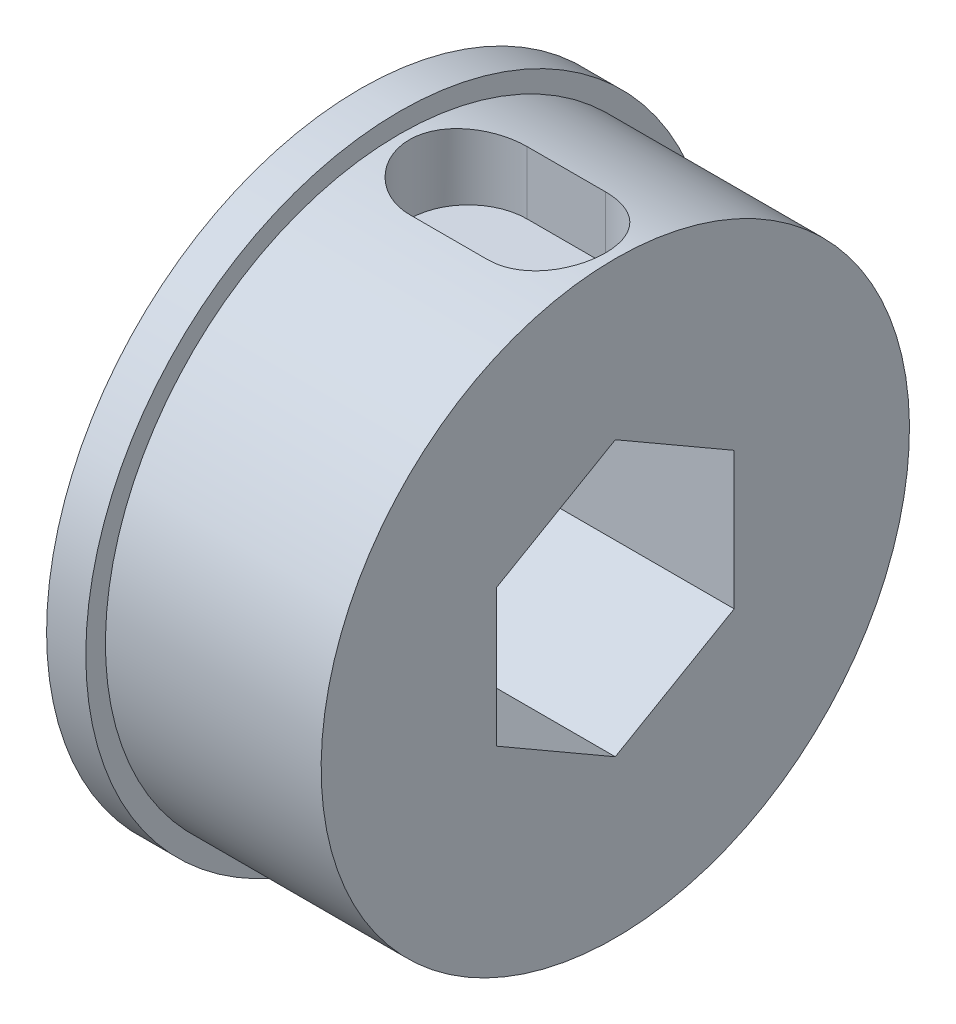
SolidWorks part; units mm, degrees
ref_plane "Front Plane" through (0, 0, 0) normal (0, 0, 1) x (1, 0, 0)
ref_plane "Top Plane" through (0, 0, 0) normal (0, 1, 0) x (1, 0, 0)
ref_plane "Right Plane" through (0, 0, 0) normal (1, 0, 0) x (0, 0, -1)
sketch "Sketch1" plane through (0, 0, 0) normal (0, 0, 1) x (1, 0, 0)
  line L0 (0, 0) -> (0, 16)
  line L4 (13, 15) -> (13, 0)
  line L5 (13, 0) -> (0, 0)
  line L6 (13, 15) -> (2, 15)
  line L7 (2, 15) -> (2, 16)
  line L8 (2, 16) -> (0, 16)
  point P3 (0, 0)
  point P9 (0.3417, 18.1229)
  dimension "D1" = 15
  dimension "D2" = 16
  dimension "D3" = 2
  dimension "D4" = 13
revolve "Revolve1" add sketch "Sketch1" angle 360 about L5
sketch "Sketch2" plane through (13, 0, 0) normal (1, 0, 0) x (0, 0, -1)
  line L0 (0, 7) -> (0, -7) construction
  line L1 (0, 7) -> (-6.0622, 3.5)
  line L2 (-6.0622, 3.5) -> (-6.0622, -3.5)
  line L3 (-6.0622, -3.5) -> (0, -7)
  line L4 (0, -7) -> (6.0622, -3.5)
  line L5 (6.0622, -3.5) -> (6.0622, 3.5)
  line L6 (6.0622, 3.5) -> (0, 7)
  circle A0 centre (0, 0) radius 7 construction
  dimension "D1" = 14
extrude "Cut-Extrude1" cut sketch "Sketch2" against normal through all contours L1 L2 L3 L4 L5 L6
ref_plane "Plane1" through (0, 15, 0) normal (0, 1, 0) x (1, 0, 0)
sketch "Sketch3" plane through (0, 15, 0) normal (0, 1, 0) x (1, 0, 0)
  line L0 (5.5, 0) -> (9.5, 0) construction
  line L1 (5.5, 3) -> (9.5, 3)
  line L2 (5.5, -3) -> (9.5, -3)
  line L3 (13, 0) -> (2, 0) construction
  line L4 (2, -15) -> (2, 15) construction
  line L5 (13, -15) -> (13, 15) construction
  arc A0 (5.5, 3) -> (5.5, -3) centre (5.5, 0) ccw
  arc A1 (9.5, -3) -> (9.5, 3) centre (9.5, 0) ccw
  point P3 (7.5, 0)
  point P8 (2.8231, 0)
  point P11 (0, 0)
  point P14 (12.6179, 0)
  point P17 (0, 0)
  dimension "D1" = 3
  dimension "D2" = 4
extrude "Cut-Extrude2" cut sketch "Sketch3" against normal blind 3.5
